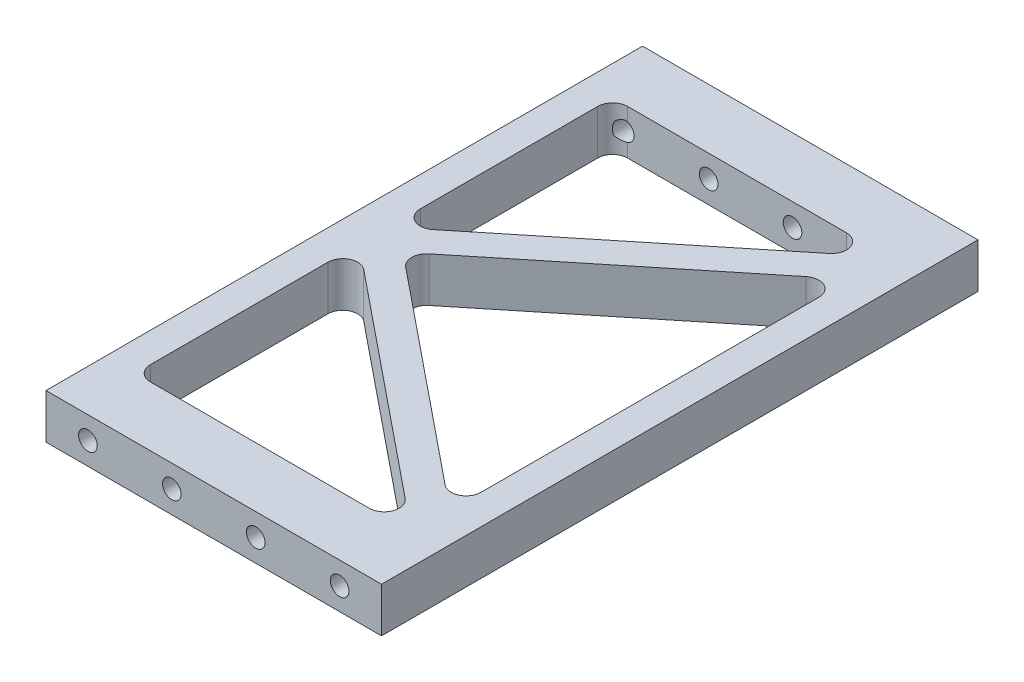
SolidWorks part; units mm, degrees
material "Сплав 2024"
ref_plane "Спереди" through (0, 0, 0) normal (0, 0, 1) x (1, 0, 0)
ref_plane "Сверху" through (0, 0, 0) normal (0, 1, 0) x (1, 0, 0)
ref_plane "Справа" through (0, 0, 0) normal (1, 0, 0) x (0, 0, -1)
sketch "Эскиз1" plane through (0, 0, 0) normal (0, 1, 0) x (1, 0, 0)
  line L2 (-15.9099, 15.9099) -> (15.9099, -15.9099) construction
  line L3 (15.9099, 15.9099) -> (-15.9099, -15.9099) construction
  line L4 (-22.5, 0) -> (-22.5, -80)
  line L5 (-22.5, -80) -> (22.5, -80)
  line L6 (22.5, 0) -> (22.5, -80)
  line L7 (-22.5, 0) -> (22.5, 0)
  dimension "D1" = 80
  dimension "D2" = 45
  dimension "D3" = 45
extrude "Бобышка-Вытянуть1" add sketch "Эскиз1" along normal blind 6
sketch "Эскиз2" plane through (0, 6, 0) normal (0, 1, 0) x (1, 0, 0)
  line L2 (0, 0) -> (0, -80) construction
  line L3 (-22.5, -80) -> (22.5, -80) construction
  line L4 (-12.3744, -52.3744) -> (12.3744, -27.6256) construction
  line L5 (-12.3744, 10) -> (-12.3744, -90) construction
  line L6 (-10.2744, 10) -> (-10.2744, -90)
  line L7 (-14.4744, 10) -> (-14.4744, -90)
  line L8 (-12.3744, -27.6256) -> (12.3744, -52.3744) construction
  line L9 (12.3744, 10) -> (12.3744, -90) construction
  line L10 (10.2744, 10) -> (10.2744, -90)
  line L11 (14.4744, 10) -> (14.4744, -90)
  line L13 (-22.5, -40) -> (22.5, -40) construction
  line L14 (-22.5, 0) -> (-22.5, -80) construction
  line L15 (22.5, -80) -> (22.5, 0) construction
  circle A0 centre (0, -40) radius 6 construction
  circle A1 centre (0, -40) radius 17.5 construction
  arc A2 (-10.2744, 10) -> (-14.4744, 10) centre (-12.3744, 10) ccw
  arc A3 (-14.4744, -90) -> (-10.2744, -90) centre (-12.3744, -90) ccw
  arc A4 (10.2744, 10) -> (14.4744, 10) centre (12.3744, 10) cw
  arc A5 (14.4744, -90) -> (10.2744, -90) centre (12.3744, -90) cw
  point P13 (12.3744, -40)
  point P18 (-12.3744, -40)
  point P37 (0, -123.5)
  dimension "D1" = 12
  dimension "D2" = 35
  dimension "D4" = 2.1
  dimension "D3" = 45
  dimension "D5" = 100
hole_wizard "Цековка для  винта с полукруглой головкой M31" [suppressed] positions "Эскиз4" profile "Эскиз5" counterbore size "M3" standard "Ansi Metric"
sketch "Эскиз4" plane through (0, 6, 0) normal (0, 1, 0) x (1, 0, 0)
  line L2 (-36.6046, 36.6046) -> (36.6046, -36.6046) construction
  line L3 (-12.3744, -12.3744) -> (12.3744, 12.3744) construction
  circle A0 centre (0, 0) radius 6 construction
  point P0 (-4.2426, 4.2426)
  point P6 (-4.2426, -4.2426)
  point P10 (4.2426, -4.2426)
  point P12 (4.2426, 4.2426)
sketch "Эскиз5" plane through (-4.2426, 6, -4.2426) normal (1, 0, 0) x (0, 0, 1)
  line L0 (0, 0) -> (0, 6)
  line L1 (0, 6) -> (1.7, 6)
  line L3 (1.7, 6) -> (1.7, 2)
  line L4 (1.7, 2) -> (3.35, 2)
  line L5 (3.35, 2) -> (3.35, 0)
  line L7 (3.35, 0) -> (0, 0)
  line L11 (0, -6.35) -> (0, 107.95) construction
  dimension "Диаметр сквозного отверстия" = 3.4
  dimension "Глубина сквозного отверстия" = 6
  dimension "Диаметр цековки" = 6.7
  dimension "Глубина цековки" = 2
hole_wizard "Отверстие обработанное метчиком M4x0.71" [suppressed] positions "Эскиз7" profile "Эскиз6" tap size "M4x0.7" standard "Ansi Metric"
sketch "Эскиз7" [suppressed] plane through (0, 4, 0) normal (0, 1, 0) x (1, 0, 0)
  line L0 (22.5, 0) -> (-22.5, 0) construction
  line L1 (0, 22.5) -> (0, -22.5) construction
  circle A0 centre (0, 0) radius 19.25 construction
  point P0 (-19.25, 0)
  point P6 (0, -19.25)
  point P10 (19.25, 0)
  point P12 (0, 19.25)
sketch "Эскиз6" plane through (-19.25, 4, 0) normal (1, 0, 0) x (0, 0, 1)
  line L0 (0, 0) -> (0, 4)
  line L1 (0, 4) -> (1.65, 4)
  line L2 (1.65, 4) -> (1.65, 0)
  line L5 (1.65, 0) -> (0, 0)
  line L11 (0, -6.35) -> (0, 107.95) construction
  dimension "Диаметр резьбы" = 3.3
  dimension "Глубина проходного сверла" = 4
extrude "Вырез-Вытянуть1" [suppressed] cut sketch "Эскиз2" against normal through all
sketch "Эскиз8" plane through (0, 0, 80) normal (0, 0, 1) x (1, 0, 0)
  line L0 (-22.5, 3) -> (22.5, 3) construction
  line L1 (-22.5, 6) -> (-22.5, 0) construction
  line L2 (22.5, 6) -> (22.5, 0) construction
  line L3 (-16.875, 6) -> (-16.875, 0) construction
  line L4 (-22.5, 6) -> (22.5, 6) construction
  line L5 (-22.5, 0) -> (22.5, 0) construction
  line L6 (-11.25, 6) -> (-11.25, 0) construction
  line L7 (-5.625, 6) -> (-5.625, 0) construction
  line L8 (0, 6) -> (0, 0) construction
  line L9 (5.625, 6) -> (5.625, 0) construction
  line L10 (11.25, 6) -> (11.25, 0) construction
  line L11 (16.875, 6) -> (16.875, 0) construction
  dimension "D1" = 45
  dimension "D2" = 5.625
  dimension "D3" = 5.625
  dimension "D4" = 5.625
  dimension "D5" = 5.625
  dimension "D6" = 5.625
  dimension "D7" = 5.625
  dimension "D8" = 5.625
sketch "Эскиз13" plane through (0, 6, 0) normal (0, 1, 0) x (1, 0, 0)
  line L0 (-18.5, 0) -> (-18.5, -80) construction
  line L1 (22.5, 0) -> (-22.5, 0) construction
  line L2 (-22.5, -80) -> (22.5, -80) construction
  line L3 (18.5, 0) -> (18.5, -80) construction
  line L4 (-22.5, -72) -> (22.5, -72) construction
  line L5 (-22.5, 0) -> (-22.5, -80) construction
  line L6 (22.5, -80) -> (22.5, 0) construction
  line L7 (-22.5, -8) -> (22.5, -8) construction
  line L8 (22.5, -4.7568) -> (-18.7822, -38.2288) construction
  line L9 (-32.8409, -30.3722) -> (17.7355, -71.3801) construction
  line L10 (-18.5, -8) -> (18.5, -8)
  line L11 (-26.2522, -38) -> (27.2799, -38) construction
  line L12 (-24.8337, -42) -> (28.2346, -42) construction
  line L13 (18.5, -40) -> (-22.5, -40) construction
  line L14 (18.5, -8) -> (-18.5, -38)
  line L15 (-18.5, -38) -> (-18.5, -8)
  line L16 (18.5, -72) -> (-18.5, -42)
  line L17 (-18.5, -42) -> (-18.5, -72)
  line L18 (-18.5, -72) -> (18.5, -72)
  line L19 (18.5, -13.1496) -> (-14.6155, -40)
  line L20 (18.5, -66.8504) -> (-14.6155, -40)
  line L21 (18.5, -13.1496) -> (18.5, -66.8504)
  point P16 (18.5, -72)
  point P32 (-18.5, -42)
  dimension "D1" = 4
  dimension "D2" = 4
  dimension "D3" = 8
  dimension "D4" = 8
  dimension "D5" = 2
  dimension "D6" = 2
  dimension "D7" = 4
extrude "Вырез-Вытянуть2" cut sketch "Эскиз13" against normal through all
fillet "Скругление10" radius 2 9 edges at (-14.6155, 3, 40) (18.5, 3, 13.1496) (18.5, 3, 66.8504) (18.5, 3, 72) (-18.5, 3, 72) (-18.5, 3, 42) (18.5, 3, 8) (-18.5, 3, 8) (-18.5, 3, 38)
chamfer "Фаска1" [suppressed] distance 1 angle 45
hole_wizard "Отверстие обработанное метчиком M3x0.52" positions "Эскиз12" profile "Эскиз11" tap size "M3x0.5" standard "Ansi Metric"
sketch "Эскиз12" plane through (0, 0, 0) normal (0, 0, -1) x (-1, 0, 0)
  line L3 (16.875, 6) -> (16.875, 0) construction
  line L4 (-16.875, 6) -> (-16.875, 0) construction
  line L5 (-5.625, 6) -> (-5.625, 0) construction
  line L6 (5.625, 6) -> (5.625, 0) construction
  point P0 (-16.875, 3)
  point P4 (-5.625, 3)
  point P8 (5.625, 3)
  point P12 (16.875, 3)
sketch "Эскиз11" plane through (16.875, 3, 0) normal (1, 0, 0) x (0, 1, 0)
  line L0 (0, 0) -> (0, 9.2511)
  line L1 (0, 9.2511) -> (1.25, 8.5)
  line L2 (1.25, 8.5) -> (1.25, 0)
  line L5 (1.25, 0) -> (0, 0)
  line L10 (0, 9.2511) -> (-1.25, 8.5) construction
  line L11 (0, -6.35) -> (0, 107.95) construction
  dimension "Диаметр сверла" = 2.5
  dimension "Глубина сверла" = 8.5
  dimension "Угол заточки сверла" = 118
cosmetic thread "Отверстие резьбы5" parameters "D1"=6, "D2"=3
cosmetic thread "Отверстие резьбы6" parameters "D1"=6, "D2"=3
cosmetic thread "Отверстие резьбы7" parameters "D1"=6, "D2"=3
cosmetic thread "Отверстие резьбы8" parameters "D1"=6, "D2"=3
hole_wizard "Отверстие обработанное метчиком M3x0.51" positions "Эскиз10" profile "Эскиз9" tap size "M3x0.5" standard "Ansi Metric"
sketch "Эскиз10" plane through (0, 0, 80) normal (0, 0, 1) x (1, 0, 0)
  line L0 (-16.875, 6) -> (-16.875, 0) construction
  line L4 (16.875, 6) -> (16.875, 0) construction
  line L5 (5.625, 6) -> (5.625, 0) construction
  line L6 (-5.625, 6) -> (-5.625, 0) construction
  point P0 (-16.875, 3)
  point P4 (-5.625, 3)
  point P8 (5.625, 3)
  point P12 (16.875, 3)
sketch "Эскиз9" plane through (-16.875, 3, 80) normal (1, 0, 0) x (0, -1, 0)
  line L0 (0, 0) -> (0, 9.2511)
  line L1 (0, 9.2511) -> (1.25, 8.5)
  line L2 (1.25, 8.5) -> (1.25, 0)
  line L5 (1.25, 0) -> (0, 0)
  line L10 (0, 9.2511) -> (-1.25, 8.5) construction
  line L11 (0, -6.35) -> (0, 107.95) construction
  dimension "Диаметр сверла" = 2.5
  dimension "Глубина сверла" = 8.5
  dimension "Угол заточки сверла" = 118
cosmetic thread "Отверстие резьбы1" parameters "D1"=6, "D2"=3
cosmetic thread "Отверстие резьбы2" parameters "D1"=6, "D2"=3
cosmetic thread "Отверстие резьбы3" parameters "D1"=6, "D2"=3
cosmetic thread "Отверстие резьбы4" parameters "D1"=6, "D2"=3
equation "\"D2@Эскиз8\"=\"D1@Эскиз8\"/8"
equation "\"D3@Эскиз8\"=\"D2@Эскиз8\""
equation "\"D4@Эскиз8\"=\"D2@Эскиз8\""
equation "\"D5@Эскиз8\"=\"D2@Эскиз8\""
equation "\"D6@Эскиз8\"=\"D2@Эскиз8\""
equation "\"D7@Эскиз8\"=\"D2@Эскиз8\""
equation "\"D8@Эскиз8\"=\"D2@Эскиз8\""
